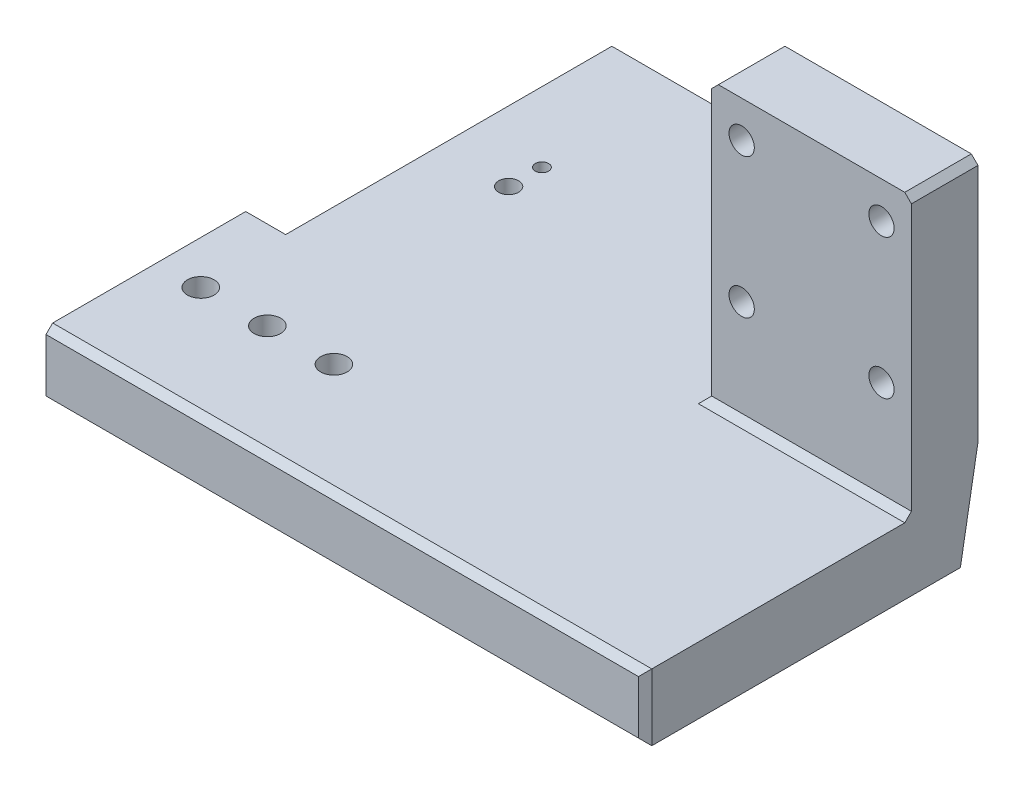
SolidWorks part; units mm, degrees
ref_plane "Front Plane" through (0, 0, 0) normal (0, 0, 1) x (1, 0, 0)
ref_plane "Top Plane" through (0, 0, 0) normal (0, 1, 0) x (1, 0, 0)
ref_plane "Right Plane" through (0, 0, 0) normal (1, 0, 0) x (0, 0, -1)
sketch "Sketch1" plane through (0, 0, 0) normal (0, 0, 1) x (1, 0, 0)
  line L1 (0, 0) -> (30, 0)
  line L2 (0, 0) -> (0, 32)
  line L3 (0, 32) -> (30, 32)
  line L4 (30, 0) -> (30, 32)
  line L5 (25.5, 26.5) -> (4.5, 26.5)
  line L6 (25.5, 26.5) -> (25.5, 5.5)
  line L7 (25.5, 5.5) -> (4.5, 5.5)
  line L8 (4.5, 26.5) -> (4.5, 5.5)
  line L9 (0, 0) -> (30, 0)
  line L10 (0, 0) -> (0, -20)
  line L11 (0, -20) -> (30, -20)
  line L12 (30, 0) -> (30, -20)
  circle A0 centre (4.5, 26.5) radius 1.9
  circle A1 centre (4.5, 5.5) radius 1.9
  circle A2 centre (25.5, 5.5) radius 1.9
  circle A3 centre (25.5, 26.5) radius 1.9
  point P9 (25.5, 16)
  point P10 (30, 16)
  point P11 (15, 5.5)
  point P12 (15, 0)
  dimension "D4" = 3.8
  dimension "D1" = 30
  dimension "D2" = 32
  dimension "D3" = 21
  dimension "D5" = 20
extrude "Boss-Extrude1" add sketch "Sketch1" along normal blind 10 contours A3 L5 A0 L8 A1 L7 A2 L6 | L1 L4 L3 L2 A3 L6 A2 L7 A1 L8 A0 L5 | L12 L1 L10 L11
chamfer "Chamfer1" distance 15 angle 10 1 edges at (15, -20, 0)
sketch "Sketch2" plane through (0, -20, 0) normal (0, -1, 0) x (1, 0, 0)
  line L1 (30, 10) -> (-55, 10)
  line L2 (30, 10) -> (30, 50)
  line L3 (30, 50) -> (-55, 50)
  line L4 (-55, 10) -> (-55, 50)
  line L5 (-55, 10) -> (-5, 10)
  line L6 (-55, 10) -> (-55, -30)
  line L7 (-55, -30) -> (-5, -30)
  line L8 (-5, 10) -> (-5, -30)
  line L9 (0, 2.6449) -> (-5, 2.6449)
  line L10 (0, 2.6449) -> (0, 10)
  line L11 (0, 10) -> (-5, 10)
  line L12 (-5, 2.6449) -> (-5, 10)
  line L13 (-55, 50) -> (-60, 50)
  line L14 (-55, 50) -> (-55, 20)
  line L15 (-55, 20) -> (-60, 20)
  line L16 (-60, 50) -> (-60, 20)
  line M8 (30, 10) -> (0, 10)
  dimension "D1" = 85
  dimension "D2" = 40
  dimension "D3" = 50
  dimension "D4" = 40
  dimension "D5" = 5
  dimension "D6" = 30
extrude "Boss-Extrude2" add sketch "Sketch2" against normal blind 10 contours L4 L1 L2 L3 M8 | L8 L1 L6 L7 | L10 L9 L12 L11 | L14 L13 L16 L15
sketch "Sketch3" plane through (0, -10, 0) normal (0, 1, 0) x (1, 0, 0)
  line L0 (-43.5, 8) -> (-43.5, 3) construction
  line L1 (-53.5, -33.25) -> (-43.5, -33.25) construction
  line L2 (-43.5, -33.25) -> (-33.5, -33.25) construction
  circle A0 centre (-43.5, 8) radius 1
  circle A1 centre (-43.5, 3) radius 1.5
  circle A2 centre (-33.5, -33.25) radius 2
  circle A3 centre (-53.5, -33.25) radius 2
  circle A4 centre (-43.5, -33.25) radius 2
  dimension "D3" = 2
  dimension "D4" = 3
  dimension "D7" = 4
  dimension "D8" = 4
  dimension "D9" = 10
  dimension "D1" = 22
  dimension "D2" = 11.5
  dimension "D5" = 5
  dimension "D6" = 41.25
extrude "Cut-Extrude1" cut sketch "Sketch3" against normal blind 35 contours A3 | A4 | A2 | A0 | A1
chamfer "Chamfer2" distance 1 angle 45 13 edges at (0, -10, 6.3225) (15, -10, 10) (30, 32, 5) (0, 32, 5) (-15, -20, 50) (-15, -10, 50) (30, -15, 50) (-30, -20, -30) (-30, -10, -30) (-5, -15, -30) (-55, -15, -30) (-55, -10, -5) (-55, -20, -5)
